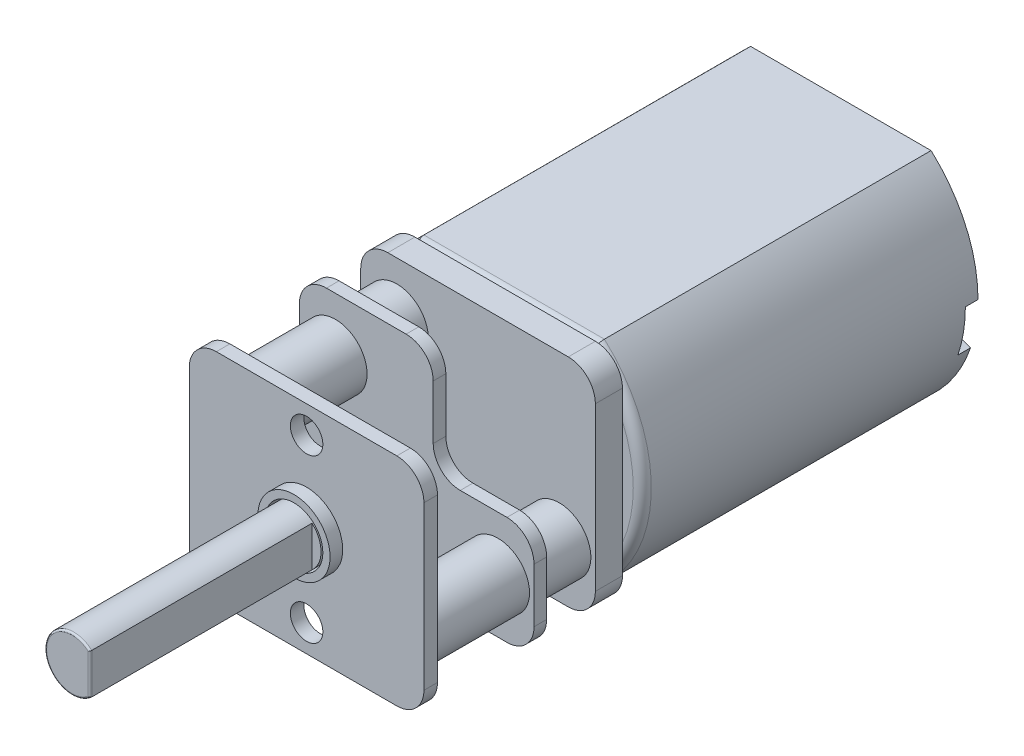
SolidWorks part; units mm, degrees
ref_plane "Front Plane" through (0, 0, 0) normal (0, 0, 1) x (1, 0, 0)
ref_plane "Top Plane" through (0, 0, 0) normal (0, 1, 0) x (1, 0, 0)
ref_plane "Right Plane" through (0, 0, 0) normal (1, 0, 0) x (0, 0, -1)
sketch "Sketch1" plane through (0, 0, 0) normal (0, 0, 1) x (1, 0, 0)
  line L0 (-5, 5.85) -> (5, 5.85)
  line L1 (5, -5.85) -> (-5, -5.85)
  line L2 (0, 11.7732) -> (0, -11.2069) construction
  arc A2 (5, 5.85) -> (5, -5.85) centre (-0.2812, 0) cw
  arc A3 (-5, 5.85) -> (-5, -5.85) centre (0.2812, 0) ccw
  point P6 (0, 5.85)
  point P7 (0, -5.85)
  point P11 (-7.6, 0)
  point P12 (7.6, 0)
  dimension "D2" = 10
  dimension "D3" = 15.2
  dimension "D1" = 11.7
extrude "Motor" add sketch "Sketch1" along normal blind 18.6
sketch "Sketch2" plane through (0, 0, 0) normal (0, 0, -1) x (-1, 0, 0)
  circle A0 centre (0, 0) radius 2.75
  dimension "D1" = 5.5
extrude "Boss-Extrude2" add sketch "Sketch2" along normal blind 0.8
fillet "Fillet1" radius 0.5 4 edges at (0, 5.85, 18.6) (7.6, 0, 18.6) (0, -5.85, 18.6) (-7.6, 0, 18.6)
sketch "Sketch3" plane through (0, 0, 18.6) normal (0, 0, 1) x (1, 0, 0)
  line L1 (-6.5, -6) -> (6.5, -6)
  line L2 (-6.5, -6) -> (-6.5, 6)
  line L3 (-6.5, 6) -> (6.5, 6)
  line L4 (6.5, -6) -> (6.5, 6)
  line L5 (-6.5, -6) -> (6.5, 6) construction
  line L6 (-6.5, 6) -> (6.5, -6) construction
  point P0 (0, 0)
  dimension "D1" = 13
  dimension "D2" = 12
extrude "reductor_base" add sketch "Sketch3" along normal blind 1.5
sketch "Sketch4" plane through (0, 0, 20.1) normal (0, 0, 1) x (1, 0, 0)
  line L0 (6.5, 6) -> (-6.5, 6) construction
  line L1 (-6.5, 6) -> (-6.5, -6) construction
  line L2 (-6.5, -6) -> (6.5, -6) construction
  line L3 (6.5, -6) -> (6.5, 6) construction
  circle A0 centre (-4.5, 3) radius 1.75
  circle A1 centre (4.5, -3) radius 1.75
  dimension "D1" = 3.5
  dimension "D2" = 3
  dimension "D3" = 2
  dimension "D4" = 3
  dimension "D5" = 2
extrude "reductor_support" add sketch "Sketch4" along normal blind 9.5
sketch "Sketch5" plane through (0, 0, 29.6) normal (0, 0, 1) x (1, 0, 0)
  line L1 (6.5, -6) -> (-6.5, -6)
  line L2 (6.5, -6) -> (6.5, 6)
  line L3 (6.5, 6) -> (-6.5, 6)
  line L4 (-6.5, -6) -> (-6.5, 6)
  line L5 (6.5, -6) -> (-6.5, 6) construction
  line L6 (6.5, 6) -> (-6.5, -6) construction
  point P0 (0, 0)
extrude "reductor_ceil" add sketch "Sketch5" against normal blind 0.75
fillet "Fillet2" radius 1.5 8 edges at (6.5, 6, 29.225) (-6.5, 6, 29.225) (6.5, -6, 29.225) (-6.5, -6, 29.225) (6.5, -6, 19.35) (-6.5, -6, 19.35) (-6.5, 6, 19.35) (6.5, 6, 19.35)
sketch "Sketch6" plane through (0, 0, 29.6) normal (0, 0, 1) x (1, 0, 0)
  circle A0 centre (0, 0) radius 2
  circle A1 centre (0, 0) radius 1.6
  dimension "D1" = 4
  dimension "D2" = 3.2
extrude "shaft_ring" add sketch "Sketch6" along normal blind 0.7
sketch "Sketch7" plane through (0, 0, 29.6) normal (0, 0, 1) x (1, 0, 0)
  circle A0 centre (0, 0) radius 1.5
  dimension "D1" = 3
extrude "shaft" add sketch "Sketch7" along normal blind 13 separate body
sketch "Sketch8" plane through (0, 0, 42.6) normal (0, 0, 1) x (1, 0, 0)
  line L0 (1, 1.118) -> (1, -1.118)
  circle A0 centre (0, 0) radius 1.5 construction
  arc A1 (1, 1.118) -> (1, -1.118) centre (0, 0) cw
  point P4 (-1.5, 0)
  dimension "D1" = 2.5
extrude "shaft_D_trim" cut sketch "Sketch8" against normal blind 12.3
sketch "Sketch9" plane through (0, 0, 29.6) normal (0, 0, 1) x (1, 0, 0)
  line L0 (-8.1232, 0) -> (10.4999, 0) construction
  circle A0 centre (0, 4.5) radius 0.9
  circle A1 centre (0, -4.5) radius 0.9
  dimension "D2" = 1.8
  dimension "D1" = 9
extrude "mount_hole" cut sketch "Sketch9" against normal up to surface (0.75 mm away) up to face at (-2.75, 3, 28.85)
sketch "Sketch12" plane through (0, 0, 0) normal (0, 0, -1) x (-1, 0, 0)
  line L0 (7.186, 2.5208) -> (2.6431, 0.7594)
  line L1 (7.6, 0) -> (0.883, -2.6044)
  line L2 (-0.883, 2.6044) -> (-7.6, 0)
  line L3 (-7.186, -2.5208) -> (-2.6431, -0.7594)
  arc A0 (5, -5.85) -> (5, 5.85) centre (-0.2812, 0) ccw construction
  circle A1 centre (0, 0) radius 2.75 construction
  arc A2 (-5, 5.85) -> (-5, -5.85) centre (0.2812, 0) ccw construction
  arc A3 (2.6431, 0.7594) -> (0.883, -2.6044) centre (0, 0) cw
  arc A4 (-2.6431, -0.7594) -> (-0.883, 2.6044) centre (0, 0) cw
  arc A5 (7.186, 2.5208) -> (7.6, 0) centre (-0.2812, 0) cw
  arc A6 (-7.186, -2.5208) -> (-7.6, 0) centre (0.2812, 0) cw
  circle M5 centre (0, 0) radius 2.75
  arc M6 (5, -5.85) -> (5, 5.85) centre (-0.2812, 0) ccw
  arc M8 (-5, 5.85) -> (-5, -5.85) centre (0.2812, 0) ccw
  dimension "D1" = 2.5
  dimension "D2" = 2.5
extrude "Cut-Extrude8" cut sketch "Sketch12" against normal blind 0.7 contours L3 L2 M8 M5 | L1 L0 M6 M5
sketch "Sketch13" plane through (0, 0, 0.7) normal (0, 0, -1) x (-1, 0, 0)
  line L0 (3.9028, 0.999) -> (4.6258, -0.8657)
  line L1 (4.6258, -0.8657) -> (5.092, -0.6849)
  line L2 (5.092, -0.6849) -> (4.369, 1.1798)
  line L3 (4.369, 1.1798) -> (3.9028, 0.999)
  line L4 (-5.1114, 0.7351) -> (-4.3884, -1.1297)
  line L5 (-4.3884, -1.1297) -> (-3.9222, -0.9489)
  line L6 (-3.9222, -0.9489) -> (-4.6452, 0.9158)
  line L7 (-4.6452, 0.9158) -> (-5.1114, 0.7351)
  dimension "D1" = 0.5
  dimension "D2" = 2
  dimension "D3" = 4
  dimension "D4" = 4
extrude "pins" add sketch "Sketch13" along normal blind 2.5
fillet "Fillet4" radius 0.6 4 edges at (4.1553, -1.0393, -1.8) (4.8783, 0.8255, -1.8) (-4.8589, -0.7753, -1.8) (-4.1359, 1.0894, -1.8)
fillet "Fillet5" radius 0.1 2 edges at (1, 0, 42.6) (-1.5, 0, 42.6)
ref_plane "Plane1" through (0, 0, 23.5) normal (0, 0, 1) x (1, 0, 0)
sketch "Sketch15" plane through (0, 0, 23.5) normal (0, 0, 1) x (1, 0, 0)
  line L4 (0.9144, 4.5) -> (0.9144, 1.5)
  line L5 (2.4144, 0) -> (5, 0)
  line L8 (-5, -6) -> (5, -6)
  line L9 (6.5, -4.5) -> (6.5, 4.5)
  line L10 (5, 6) -> (-5, 6)
  line L11 (-6.5, 4.5) -> (-6.5, -4.5)
  line L12 (-5, -6) -> (5, -6)
  line L13 (6.5, -4.5) -> (6.5, -1.5)
  line L14 (-0.5856, 6) -> (-5, 6)
  line L15 (-6.5, 4.5) -> (-6.5, -4.5)
  arc A4 (5, 0) -> (6.5, -1.5) centre (5, -1.5) cw
  arc A5 (0.9144, 4.5) -> (-0.5856, 6) centre (-0.5856, 4.5) ccw
  arc A6 (0.9144, 1.5) -> (2.4144, 0) centre (2.4144, 1.5) ccw
  arc A8 (5, -6) -> (6.5, -4.5) centre (5, -4.5) ccw
  arc A9 (6.5, 4.5) -> (5, 6) centre (5, 4.5) ccw
  arc A10 (-5, 6) -> (-6.5, 4.5) centre (-5, 4.5) ccw
  arc A11 (-6.5, -4.5) -> (-5, -6) centre (-5, -4.5) ccw
  arc A12 (5, -6) -> (6.5, -4.5) centre (5, -4.5) ccw
  arc A14 (-5, 6) -> (-6.5, 4.5) centre (-5, 4.5) ccw
  arc A15 (-6.5, -4.5) -> (-5, -6) centre (-5, -4.5) ccw
  dimension "D2" = 1.5
  dimension "D1" = 0
extrude "Boss-Extrude11" add sketch "Sketch15" against normal blind 0.7
